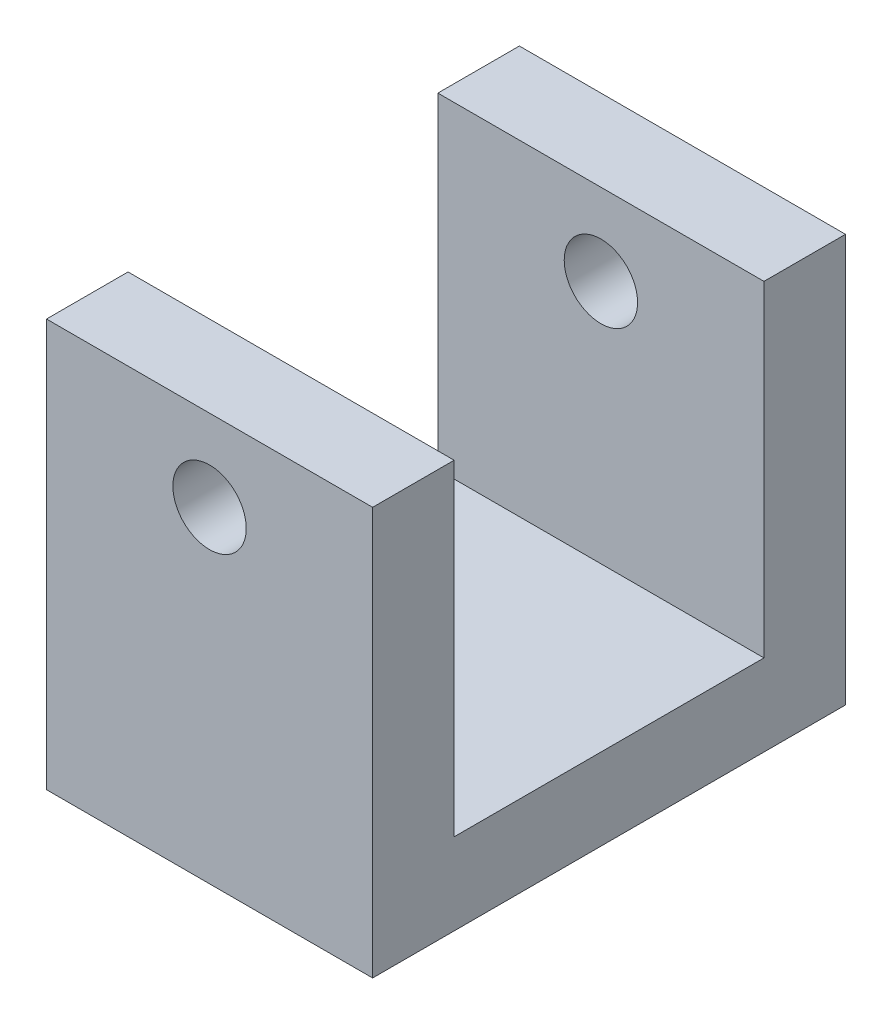
SolidWorks part; units mm, degrees
ref_plane "Front Plane" through (0, 0, 0) normal (0, 0, 1) x (1, 0, 0)
ref_plane "Top Plane" through (0, 0, 0) normal (0, 1, 0) x (1, 0, 0)
ref_plane "Right Plane" through (0, 0, 0) normal (1, 0, 0) x (0, 0, -1)
sketch "Sketch1" plane through (0, 0, 0) normal (0, 1, 0) x (1, 0, 0)
  line L1 (-10, -14.5) -> (10, -14.5)
  line L2 (-10, -14.5) -> (-10, 14.5)
  line L3 (-10, 14.5) -> (10, 14.5)
  line L4 (10, -14.5) -> (10, 14.5)
  line L5 (-10, -14.5) -> (10, 14.5) construction
  line L6 (-10, 14.5) -> (10, -14.5) construction
  point P0 (0, 0)
  dimension "D1" = 20
  dimension "D2" = 29
extrude "Boss-Extrude1" add sketch "Sketch1" along normal blind 5
sketch "Sketch2" plane through (0, 5, 0) normal (0, 1, 0) x (1, 0, 0)
  line L0 (10, -14.5) -> (10, 14.5) construction
  line L1 (-10, 14.5) -> (10, 14.5)
  line L2 (-10, 14.5) -> (-10, 9.5)
  line L3 (-10, 9.5) -> (10, 9.5)
  line L4 (10, 14.5) -> (10, 9.5)
  line L6 (-10, -14.5) -> (10, -14.5)
  line L7 (-10, -14.5) -> (-10, -9.5)
  line L8 (-10, -9.5) -> (10, -9.5)
  line L9 (10, -14.5) -> (10, -9.5)
  dimension "D1" = 5
  dimension "D2" = 19
extrude "Boss-Extrude2" add sketch "Sketch2" along normal blind 20
sketch "Sketch3" plane through (0, 0, -14.5) normal (0, 0, -1) x (-1, 0, 0)
  line L1 (-10, 0) -> (10, 0) construction
  circle A0 centre (0, 20) radius 2.25
  dimension "D1" = 4.5
  dimension "D2" = 20
extrude "Cut-Extrude1" cut sketch "Sketch3" against normal through all
